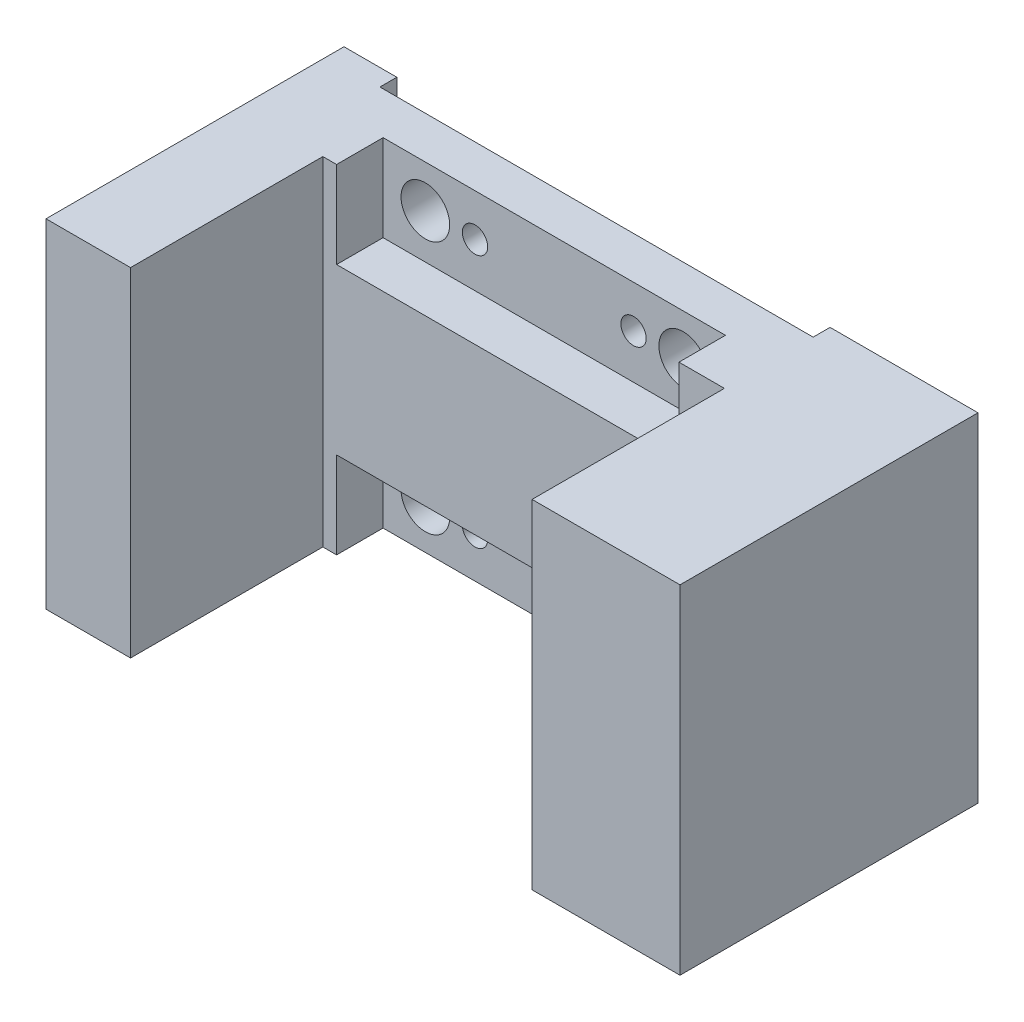
SolidWorks part; units mm, degrees
ref_plane "前视基准面" through (0, 0, 0) normal (0, 0, 1) x (1, 0, 0)
ref_plane "上视基准面" through (0, 0, 0) normal (0, 1, 0) x (1, 0, 0)
ref_plane "右视基准面" through (0, 0, 0) normal (1, 0, 0) x (0, 0, -1)
sketch "草图1" plane through (0, 0, 0) normal (0, 0, 1) x (1, 0, 0)
  line L1 (-7.5503, 16.7364) -> (22.4497, 16.7364)
  line L2 (-7.5503, 16.7364) -> (-7.5503, -11.2636)
  line L3 (-7.5503, -11.2636) -> (22.4497, -11.2636)
  line L4 (22.4497, 16.7364) -> (22.4497, -11.2636)
  dimension "D1" = 30
  dimension "D2" = 28
extrude "凸台-拉伸1" add sketch "草图1" along normal blind 10
sketch "草图2" plane through (0, 0, 0) normal (0, 0, -1) x (-1, 0, 0)
  line L0 (-22.4497, 16.7364) -> (7.5503, 16.7364) construction
  line L1 (7.5503, 16.7364) -> (7.5503, -11.2636) construction
  line L3 (5.0503, 16.7364) -> (-15.4497, 16.7364)
  line L4 (5.0503, 16.7364) -> (5.0503, 3.7364)
  line L5 (2.0503, 0.7364) -> (-12.4497, 0.7364)
  line L6 (-15.4497, 16.7364) -> (-15.4497, 3.7364)
  arc A0 (2.0503, 0.7364) -> (5.0503, 3.7364) centre (2.0503, 3.7364) ccw
  arc A1 (-12.4497, 0.7364) -> (-15.4497, 3.7364) centre (-12.4497, 3.7364) cw
  point P0 (5.0503, 16.7364)
  point P11 (5.0503, 0.7364)
  dimension "D4" = 3
  dimension "D1" = 2.5
  dimension "D2" = 20.5
  dimension "D3" = 16
extrude "切除-拉伸2" cut sketch "草图2" against normal blind 0.8
sketch "草图3" plane through (0, 0, 0.8) normal (0, 0, -1) x (-1, 0, 0)
  line L0 (5.0503, 16.7364) -> (-15.4497, 16.7364) construction
  line L2 (-15.1997, 16.7364) -> (4.8003, 16.7364)
  line L3 (-15.1997, 16.7364) -> (-15.1997, 3.7364)
  line L4 (-12.1997, 0.7364) -> (1.8003, 0.7364)
  line L5 (4.8003, 16.7364) -> (4.8003, 3.7364)
  arc A0 (1.8003, 0.7364) -> (4.8003, 3.7364) centre (1.8003, 3.7364) ccw
  arc A1 (-12.1997, 0.7364) -> (-15.1997, 3.7364) centre (-12.1997, 3.7364) cw
  point P0 (-5.1997, 16.7364)
  point P9 (4.8003, 0.7364)
  point P12 (1.8003, 10.7364)
  point P14 (-12.1997, 10.7364)
  dimension "D4" = 3
  dimension "D1" = 20
  dimension "D2" = 10
  dimension "D3" = 16
  dimension "D5" = 6
  dimension "D6" = 6
  dimension "D7" = 3
  dimension "D8" = 3
hole_wizard "M1.4x0.3 螺纹孔2" positions "草图9" profile "草图7" tap size "M1.4x0.3" standard "ANSI Metric"
sketch "草图9" plane through (0, 0, 0.8) normal (0, 0, -1) x (-1, 0, 0)
  line L0 (-15.1997, 16.7364) -> (4.8003, 16.7364) construction
  point P0 (-12.1997, 8.7364)
  point P3 (1.8003, 8.7364)
  dimension "D1" = 8
  dimension "D2" = 8
sketch "草图7" plane through (12.1997, 8.7364, 0.8) normal (1, 0, 0) x (0, 1, 0)
  line L0 (0, 0) -> (0, 4.0305)
  line L1 (0, 4.0305) -> (0.55, 3.7)
  line L2 (0.55, 3.7) -> (0.55, 0)
  line L5 (0.55, 0) -> (0, 0)
  line L10 (0, 4.0305) -> (-0.55, 3.7) construction
  line L11 (0, -6.35) -> (0, 107.95) construction
  dimension "螺纹孔钻头直径" = 1.1
  dimension "螺纹孔钻头深度" = 3.7
  dimension "导头角度" = 118
cosmetic thread "孔螺蚊线9" parameters "D1"=3.5, "D2"=1.4
cosmetic thread "孔螺蚊线10" parameters "D1"=3.5, "D2"=1.4
sketch "草图10" plane through (0, 16.7364, 0) normal (0, 1, 0) x (1, 0, 0)
  line L0 (22.4497, -0.8) -> (-7.5503, -0.8)
  line L1 (22.4497, -10) -> (22.4497, 0) construction
  line L2 (-7.5503, -10) -> (-7.5503, 0) construction
  line L3 (22.4497, 0) -> (15.4497, 0) construction
  point P8 (5.1997, -0.8)
  dimension "D1" = 0.8
  dimension "D8" = 12.75
sketch "草图12" plane through (0, 0, 0) normal (0, 0, -1) x (-1, 0, 0)
  line L0 (-22.4497, -11.2636) -> (-22.4497, 16.7364) construction
  line L1 (7.5503, -11.2636) -> (-22.4497, -11.2636)
  line L2 (7.5503, -11.2636) -> (7.5503, -7.0136)
  line L3 (7.5503, -7.0136) -> (-22.4497, -7.0136)
  line L4 (-22.4497, -11.2636) -> (-22.4497, -7.0136)
  dimension "D1" = 4.25
extrude "切除-拉伸5" cut sketch "草图12" against normal blind 10
sketch "草图14" plane through (0, 0, 10) normal (0, 0, 1) x (1, 0, 0)
  line L0 (-7.5503, -7.0136) -> (22.4497, -7.0136) construction
  line L1 (-7.5503, 16.7364) -> (15.4497, 16.7364)
  line L2 (-7.5503, 16.7364) -> (-7.5503, -7.0136)
  line L3 (-7.5503, -7.0136) -> (15.4497, -7.0136)
  line L4 (15.4497, 16.7364) -> (15.4497, -7.0136)
  line L5 (22.4497, -7.0136) -> (22.4497, 16.7364) construction
  dimension "D1" = 7
extrude "切除-拉伸7" cut sketch "草图14" against normal blind 5
sketch "草图21" plane through (0, 0, 0.8) normal (0, 0, -1) x (-1, 0, 0)
  point P0 (-5.1997, 16.7364)
sketch "草图22" plane through (0, 16.7364, 0) normal (0, 1, 0) x (1, 0, 0)
  line L0 (5.1997, -0.8) -> (5.1997, -5)
  line L1 (15.4497, -5) -> (-7.5503, -5) construction
sketch "草图23" plane through (0, 0, 5) normal (0, 0, 1) x (1, 0, 0)
  line L0 (-7.5503, -7.0136) -> (15.4497, -7.0136) construction
  line L1 (-7.5503, 16.7364) -> (-3.5503, 16.7364)
  line L2 (-7.5503, 16.7364) -> (-7.5503, -7.0136)
  line L3 (-7.5503, -7.0136) -> (-3.5503, -7.0136)
  line L4 (-3.5503, 16.7364) -> (-3.5503, -7.0136)
  dimension "D1" = 4
extrude "凸台-拉伸4" add sketch "草图23" along normal blind 9.1
sketch "草图25" plane through (0, 0, 5) normal (0, 0, 1) x (1, 0, 0)
  line L0 (-3.5503, -7.0136) -> (-3.5503, 16.7364) construction
  line L1 (15.4497, 16.7364) -> (-3.5503, 16.7364)
  line L2 (15.4497, 16.7364) -> (15.4497, 10.7364)
  line L3 (15.4497, 10.7364) -> (-3.5503, 10.7364)
  line L4 (-3.5503, 16.7364) -> (-3.5503, 10.7364)
  dimension "D1" = 6
sketch "草图31" plane through (0, 0, 10) normal (0, 0, 1) x (1, 0, 0)
  line L1 (15.4497, 16.7364) -> (22.4497, 16.7364)
  line L2 (15.4497, 16.7364) -> (15.4497, -7.0136)
  line L3 (15.4497, -7.0136) -> (22.4497, -7.0136)
  line L4 (22.4497, 16.7364) -> (22.4497, -7.0136)
extrude "凸台-拉伸6" add sketch "草图31" along normal blind 4.1
sketch "草图32" plane through (0, 0, 0) normal (0, 0, -1) x (-1, 0, 0)
  line L0 (7.5503, -7.0136) -> (-22.4497, -7.0136) construction
  line L1 (7.5503, -7.0136) -> (-22.4497, -7.0136)
  line L2 (7.5503, -7.0136) -> (7.5503, 0.7364)
  line L3 (7.5503, 0.7364) -> (-22.4497, 0.7364)
  line L4 (-22.4497, -7.0136) -> (-22.4497, 0.7364)
  line L5 (-22.4497, -7.0136) -> (-22.4497, 16.7364) construction
  dimension "D1" = 7.75
extrude "切除-拉伸13" cut sketch "草图32" against normal blind 20
sketch "草图33" plane through (0, 0.7364, 0) normal (0, -1, 0) x (1, 0, 0)
  line L1 (-2.0503, 0) -> (-5.0503, 0)
  line L2 (-2.0503, 0) -> (-2.0503, 0.8)
  line L3 (-2.0503, 0.8) -> (-5.0503, 0.8)
  line L4 (-5.0503, 0) -> (-5.0503, 0.8)
  line L7 (15.4497, 0) -> (15.4497, 0.8)
  line L8 (12.4497, 0.8) -> (15.4497, 0.8)
  line L9 (12.4497, 0) -> (12.4497, 0.8)
  line L10 (12.4497, 0) -> (15.4497, 0)
  dimension "D1" = 0.8
  dimension "D2" = 3
extrude "切除-拉伸14" cut sketch "草图33" against normal blind 10
sketch "草图24" plane through (0, 0, 0.8) normal (0, 0, -1) x (-1, 0, 0)
  line L0 (-15.1997, 16.7364) -> (4.8003, 16.7364) construction
  line L2 (2.9003, 16.7364) -> (-13.2997, 16.7364)
  line L3 (2.9003, 16.7364) -> (2.9003, 12.6364)
  line L4 (2.9003, 12.6364) -> (-13.2997, 12.6364)
  line L5 (-13.2997, 16.7364) -> (-13.2997, 12.6364)
  line L6 (5.0503, 8.7364) -> (-15.4497, 8.7364) construction
  line L10 (5.0503, 0.7364) -> (5.0503, 16.7364) construction
  line L11 (-15.4497, 16.7364) -> (-15.4497, 0.7364) construction
  line L12 (-13.2997, 0.7364) -> (-13.2997, 4.8364)
  line L13 (2.9003, 4.8364) -> (-13.2997, 4.8364)
  line L14 (2.9003, 0.7364) -> (2.9003, 4.8364)
  line L15 (2.9003, 0.7364) -> (-13.2997, 0.7364)
  dimension "D1" = 16.2
  dimension "D2" = 8.1
  dimension "D3" = 4.1
  dimension "D4" = 0
extrude "切除-拉伸10" cut sketch "草图24" against normal blind 5
sketch "草图29" plane through (0, 12.6364, 0) normal (0, 1, 0) x (1, 0, 0)
  line L0 (13.2997, -5) -> (13.2997, -0.8) construction
  line L1 (-2.9003, -0.8) -> (13.2997, -0.8)
  line L2 (-2.9003, -0.8) -> (-2.9003, -2.8)
  line L3 (-2.9003, -2.8) -> (13.2997, -2.8)
  line L4 (13.2997, -0.8) -> (13.2997, -2.8)
  dimension "D1" = 2
extrude "凸台-拉伸5" add sketch "草图29" along normal blind 4.1
sketch "草图35" plane through (0, 4.8364, 0) normal (0, -1, 0) x (1, 0, 0)
  line L0 (13.2997, 5) -> (13.2997, 0.8) construction
  line L1 (-2.9003, 0.8) -> (13.2997, 0.8)
  line L2 (-2.9003, 0.8) -> (-2.9003, 2.8)
  line L3 (-2.9003, 2.8) -> (13.2997, 2.8)
  line L4 (13.2997, 0.8) -> (13.2997, 2.8)
  dimension "D1" = 2
extrude "凸台-拉伸7" add sketch "草图35" along normal blind 4.1
sketch "草图30" plane through (0, 0, 0.8) normal (0, 0, -1) x (-1, 0, 0)
  line L0 (-15.1997, 16.7364) -> (4.8003, 16.7364) construction
  line L1 (-15.4497, 8.7364) -> (5.0503, 8.7364) construction
  line L2 (-15.4497, 16.7364) -> (-15.4497, 0.7364) construction
  line L3 (5.0503, 0.7364) -> (5.0503, 16.7364) construction
  circle A0 centre (0.9003, 14.7364) radius 1.15
  circle A1 centre (-11.2997, 14.7364) radius 1.15
  circle A2 centre (-8.9497, 2.7364) radius 0.6
  circle A3 centre (-1.4497, 14.7364) radius 0.6
  circle A4 centre (-8.9497, 14.7364) radius 0.6
  circle A5 centre (-1.4497, 2.7364) radius 0.6
  circle A6 centre (-11.2997, 2.7364) radius 1.15
  circle A7 centre (0.9003, 2.7364) radius 1.15
  dimension "D1" = 2.3
  dimension "D2" = 2.3
  dimension "D7" = 1.2
  dimension "D8" = 1.2
  dimension "D3" = 2
  dimension "D4" = 2
  dimension "D5" = 6.1
  dimension "D6" = 6.1
  dimension "D9" = 2
  dimension "D10" = 2
  dimension "D11" = 3.75
  dimension "D12" = 3.75
extrude "切除-拉伸12" cut sketch "草图30" against normal blind 5
sketch "草图34" plane through (0, 0, 0.8) normal (0, 0, -1) x (-1, 0, 0)
  line L0 (-15.4497, 8.7364) -> (5.0503, 8.7364) construction
  line L3 (-15.4497, 16.7364) -> (-15.4497, 0.7364) construction
  line L4 (5.0503, 0.7364) -> (5.0503, 16.7364) construction
